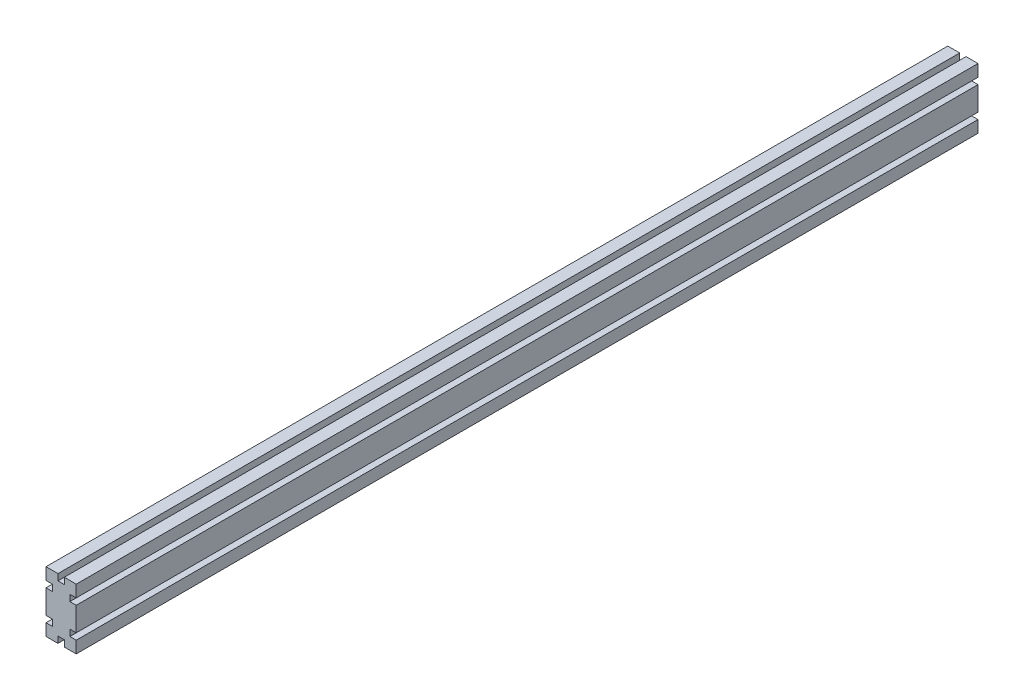
SolidWorks part; units mm, degrees
ref_plane "Front Plane" through (0, 0, 0) normal (0, 0, 1) x (1, 0, 0)
ref_plane "Top Plane" through (0, 0, 0) normal (0, 1, 0) x (1, 0, 0)
ref_plane "Right Plane" through (0, 0, 0) normal (1, 0, 0) x (0, 0, -1)
sketch "Sketch1" plane through (0, 0, 0) normal (0, 0, 1) x (1, 0, 0)
  line L0 (-19.05, -38.1) -> (-4, -38.1)
  line L1 (-4, -38.1) -> (-4, -30.1)
  line L2 (-4, -30.1) -> (4, -30.1)
  line L3 (4, -30.1) -> (4, -38.1)
  line L4 (4, -38.1) -> (19.05, -38.1)
  line L5 (19.05, -38.1) -> (19.05, -23.05)
  line L6 (19.05, -23.05) -> (11.05, -23.05)
  line L7 (11.05, -23.05) -> (11.05, -15.05)
  line L8 (11.05, -15.05) -> (19.05, -15.05)
  line L9 (19.05, -15.05) -> (19.05, 15.05)
  line L10 (19.05, 15.05) -> (11.05, 15.05)
  line L11 (11.05, 15.05) -> (11.05, 23.05)
  line L12 (11.05, 23.05) -> (19.05, 23.05)
  line L13 (19.05, 23.05) -> (19.05, 38.1)
  line L14 (19.05, 38.1) -> (4, 38.1)
  line L15 (4, 38.1) -> (4, 30.1)
  line L16 (4, 30.1) -> (-4, 30.1)
  line L17 (-4, 30.1) -> (-4, 38.1)
  line L18 (-4, 38.1) -> (-19.05, 38.1)
  line L19 (-19.05, 38.1) -> (-19.05, 23.05)
  line L20 (-19.05, 23.05) -> (-11.05, 23.05)
  line L21 (-11.05, 23.05) -> (-11.05, 15.05)
  line L22 (-11.05, 15.05) -> (-19.05, 15.05)
  line L23 (-19.05, 15.05) -> (-19.05, -15.05)
  line L24 (-19.05, -15.05) -> (-11.05, -15.05)
  line L25 (-11.05, -15.05) -> (-11.05, -23.05)
  line L26 (-11.05, -23.05) -> (-19.05, -23.05)
  line L27 (-19.05, -23.05) -> (-19.05, -38.1)
extrude "Profile" add sketch "Sketch1" along normal blind 1136.65
equation "\"length\" = 1136.65mm"
equation "\"D1@Profile\" = \"length\""
